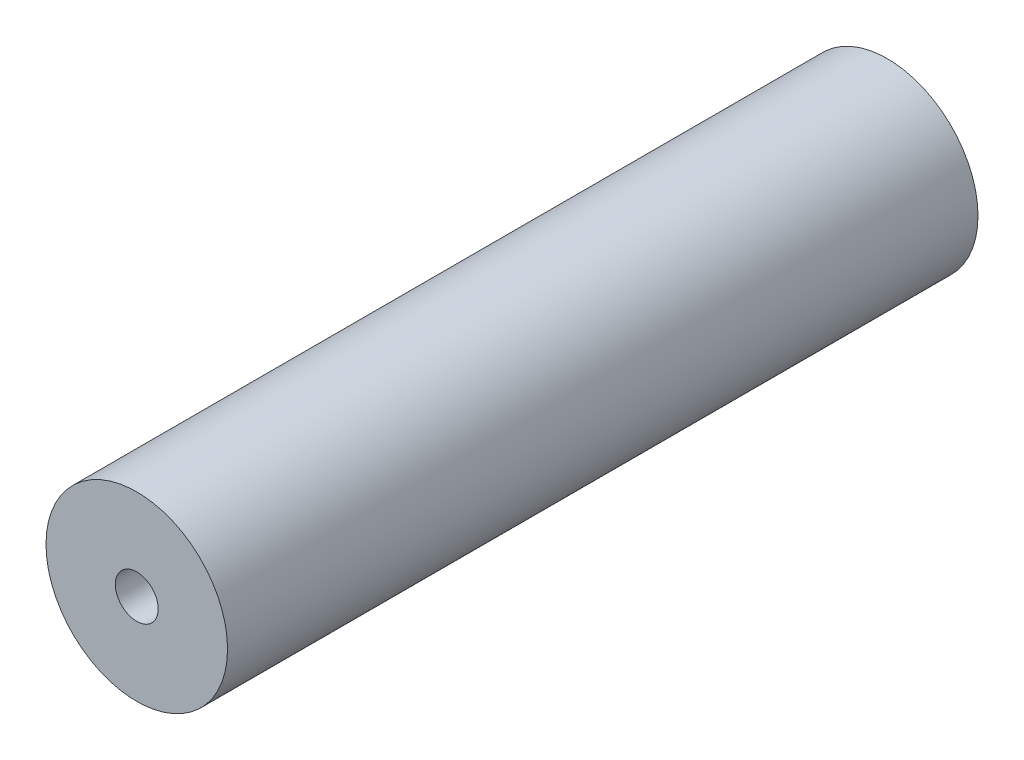
SolidWorks part; units mm, degrees
ref_plane "Front Plane" through (0, 0, 0) normal (0, 0, 1) x (1, 0, 0)
ref_plane "Top Plane" through (0, 0, 0) normal (0, 1, 0) x (1, 0, 0)
ref_plane "Right Plane" through (0, 0, 0) normal (1, 0, 0) x (0, 0, -1)
sketch "Sketch2" plane through (0, 0, 0) normal (0, 0, 1) x (1, 0, 0)
  line L0 (0, 0) -> (-80, 0) construction
  circle A0 centre (-80, 0) radius 12.7
  dimension "D2" = 25.4
  dimension "D1" = 80
extrude "Boss-Extrude1" add sketch "Sketch2" along normal mid plane 105
sketch "Sketch3" plane through (0, 0, -52.5) normal (0, 0, -1) x (-1, 0, 0)
  circle A0 centre (80, 0) radius 3
  dimension "D1" = 6
extrude "Cut-Extrude1" cut sketch "Sketch3" against normal up to next
sketch "Sketch4" plane through (0, 0, -52.5) normal (0, 0, -1) x (-1, 0, 0)
  circle A0 centre (80, 0) radius 8.5
  dimension "D1" = 17
extrude "Cut-Extrude2" cut sketch "Sketch4" against normal offset from surface (1.275 mm away) 1.275 up to face at (-83, 0, -52.5)
sketch "Sketch5" plane through (0, 0, -52.5) normal (0, 0, -1) x (-1, 0, 0)
  circle A0 centre (80, 0) radius 7.5
  dimension "D1" = 15
extrude "Cut-Extrude3" cut sketch "Sketch5" against normal offset from surface (5 mm away) 5 up to face at (-88.5, 0, -52.5)
